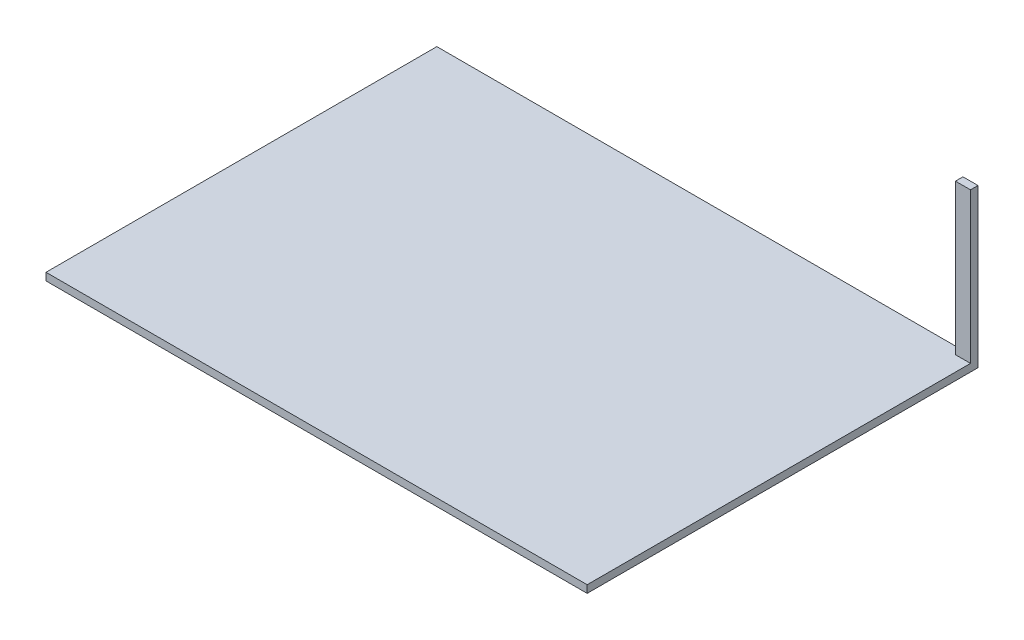
SolidWorks part; units mm, degrees
ref_plane "Plan de face" through (0, 0, 0) normal (0, 0, 1) x (1, 0, 0)
ref_plane "Plan de dessus" through (0, 0, 0) normal (0, 1, 0) x (1, 0, 0)
ref_plane "Plan de droite" through (0, 0, 0) normal (1, 0, 0) x (0, 0, -1)
sketch "Esquisse1" plane through (0, 0, 0) normal (0, 1, 0) x (1, 0, 0)
  line L1 (-180, -130) -> (180, -130)
  line L2 (-180, -130) -> (-180, 130)
  line L3 (-180, 130) -> (180, 130)
  line L4 (180, -130) -> (180, 130)
  line L5 (-180, -130) -> (180, 130) construction
  line L6 (-180, 130) -> (180, -130) construction
  point P0 (0, 0)
  dimension "D1" = 360
  dimension "D2" = 260
extrude "Boss.-Extru.1" add sketch "Esquisse1" along normal blind 5
sketch "Esquisse3" plane through (0, 5, 0) normal (0, 1, 0) x (1, 0, 0)
  line L1 (180, 130) -> (170, 130)
  line L2 (180, 130) -> (180, 125)
  line L3 (180, 125) -> (170, 125)
  line L4 (170, 130) -> (170, 125)
  dimension "D1" = 10
  dimension "D2" = 5
extrude "Boss.-Extru.3" add sketch "Esquisse3" along normal blind 100
